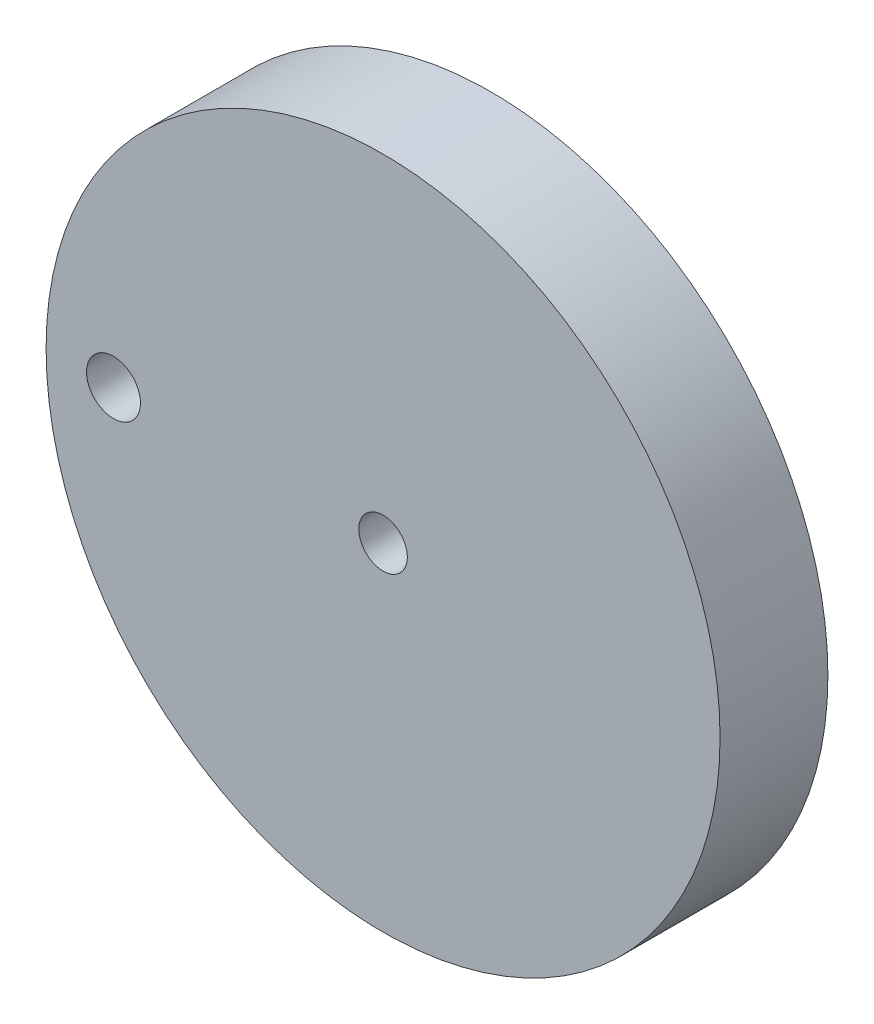
SolidWorks part; units mm, degrees
ref_plane "Front Plane" through (0, 0, 0) normal (0, 0, 1) x (1, 0, 0)
ref_plane "Top Plane" through (0, 0, 0) normal (0, 1, 0) x (1, 0, 0)
ref_plane "Right Plane" through (0, 0, 0) normal (1, 0, 0) x (0, 0, -1)
sketch "Sketch1" plane through (0, 0, 0) normal (0, 0, 1) x (1, 0, 0)
  circle A0 centre (0, 0) radius 12.5
  circle A1 centre (-10, 0) radius 1
  circle A2 centre (0, 0) radius 0.9
  dimension "D1" = 25
  dimension "D2" = 2
  dimension "D5" = 1.8
  dimension "D3" = 0
  dimension "D4" = 10
extrude "Boss-Extrude1" add sketch "Sketch1" along normal blind 4 contours A0 A2 A1
